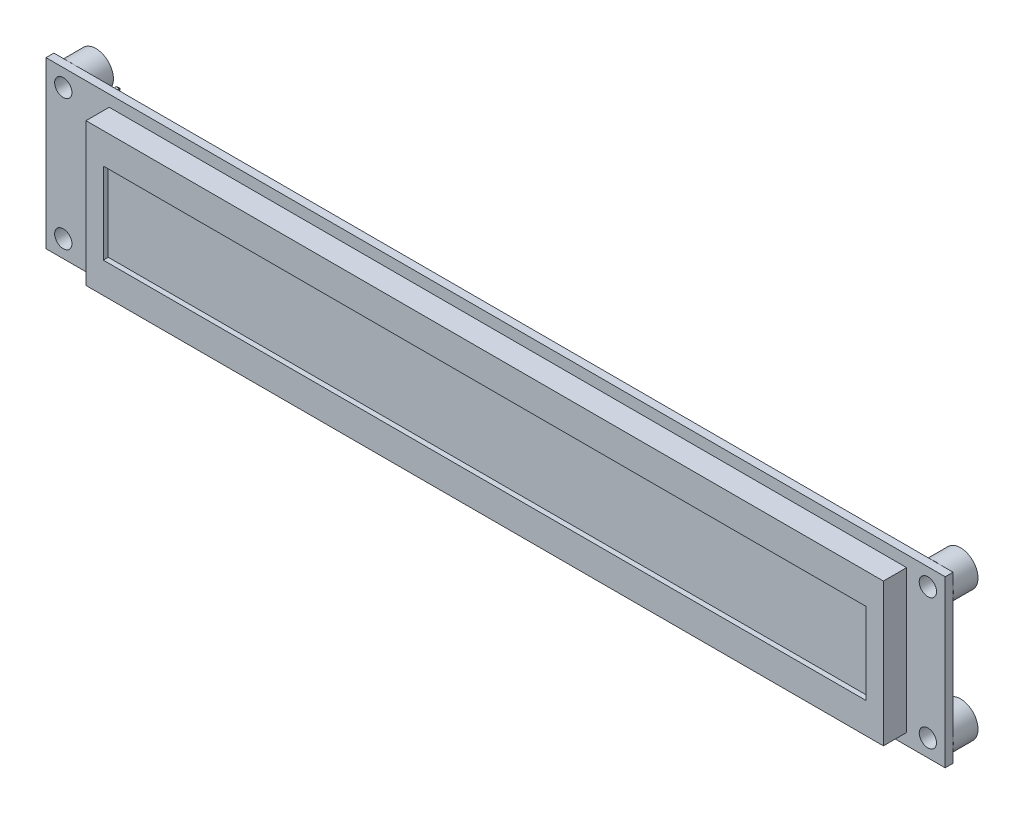
SolidWorks part; units mm, degrees
ref_plane "Спереди" through (0, 0, 0) normal (0, 0, 1) x (1, 0, 0)
ref_plane "Сверху" through (0, 0, 0) normal (0, 1, 0) x (1, 0, 0)
ref_plane "Справа" through (0, 0, 0) normal (1, 0, 0) x (0, 0, -1)
ref_plane "Плоскость4" through (0, 0, 5) normal (0, 0, 1) x (1, 0, 0)
sketch "Эскиз2" plane through (0, 0, 5) normal (0, 0, 1) x (1, 0, 0)
  line L1 (-91, -16.75) -> (91, -16.75)
  line L2 (-91, -16.75) -> (-91, 16.75)
  line L3 (-91, 16.75) -> (91, 16.75)
  line L4 (91, -16.75) -> (91, 16.75)
  line L5 (-91, -16.75) -> (91, 16.75) construction
  line L6 (-91, 16.75) -> (91, -16.75) construction
  point P0 (0, 0)
  dimension "D1" = 182
  dimension "D2" = 33.5
extrude "Бобышка-Вытянуть1" add sketch "Эскиз2" along normal blind 1.6
ref_plane "Плоскость5" through (0, 0, 0) normal (0, -1, 0) x (-1, 0, 0)
sketch "Эскиз3" plane through (0, 0, 6.6) normal (0, 0, 1) x (1, 0, 0)
  line L0 (-0.88, 0) -> (0.88, 0) construction
  line L1 (-78.2, 14.45) -> (83.2, 14.45)
  line L2 (-78.2, 14.45) -> (-78.2, -14.45)
  line L3 (-78.2, -14.45) -> (83.2, -14.45)
  line L4 (83.2, 14.45) -> (83.2, -14.45)
  line L5 (-78.2, 14.45) -> (83.2, -14.45) construction
  line L6 (-78.2, -14.45) -> (83.2, 14.45) construction
  line L7 (-91, 16.75) -> (-91, -16.75) construction
  point P0 (2.5, 0)
  dimension "D1" = 93.5
  dimension "D2" = 161.4
  dimension "D3" = 28.9
extrude "Бобышка-Вытянуть2" add sketch "Эскиз3" along normal blind 4.7
sketch "Эскиз4" plane through (0, 0, 11.3) normal (0, 0, 1) x (1, 0, 0)
  line L0 (-0.88, 0) -> (0.88, 0) construction
  line L1 (79.7, -8.25) -> (-74.7, -8.25)
  line L2 (79.7, -8.25) -> (79.7, 8.25)
  line L3 (79.7, 8.25) -> (-74.7, 8.25)
  line L4 (-74.7, -8.25) -> (-74.7, 8.25)
  line L5 (79.7, -8.25) -> (-74.7, 8.25) construction
  line L6 (79.7, 8.25) -> (-74.7, -8.25) construction
  line L7 (-91, 16.75) -> (-91, -16.75) construction
  point P0 (2.5, 0)
  dimension "D1" = 154.4
  dimension "D2" = 16.5
  dimension "D3" = 16.3
extrude "Вырез-Вытянуть1" cut sketch "Эскиз4" against normal blind 1
sketch "Эскиз5" plane through (0, 0, 6.6) normal (0, 0, 1) x (1, 0, 0)
  line L0 (-91, -16.75) -> (91, -16.75) construction
  line L1 (-91, 16.75) -> (-91, -16.75) construction
  circle A0 centre (-87.5, 13.25) radius 1.75
  circle A1 centre (-87.5, -13.25) radius 1.75
  circle A2 centre (87.5, -13.25) radius 1.75
  circle A3 centre (87.5, 13.25) radius 1.75
  dimension "D3" = 3.5
  dimension "D1" = 26.5
  dimension "D2" = 3.5
  dimension "D4" = 3.5
  dimension "D5" = 175
sketch "Эскиз6" plane through (0, 0, 5) normal (0, 0, -1) x (-1, 0, 0)
  circle A0 centre (-87.5, -13.25) radius 3.55
  circle A1 centre (-87.5, 13.25) radius 3.55
  circle A2 centre (87.5, 13.25) radius 3.55
  circle A3 centre (87.5, -13.25) radius 3.55
  dimension "D1" = 7.1
extrude "Бобышка-Вытянуть3" add sketch "Эскиз6" along normal blind 5
extrude "Вырез-Вытянуть2" cut sketch "Эскиз5" against normal through all
sketch "Эскиз7" plane through (0, 0, 0) normal (0, 0, 1) x (1, 0, 0)
  line L0 (-91, 12.6563) -> (-91, -12.6563) construction
  line L1 (-88.18, -8.51) -> (-88.82, -8.51)
  line L2 (-88.18, -8.51) -> (-88.18, -9.15)
  line L3 (-88.18, -9.15) -> (-88.82, -9.15)
  line L4 (-88.82, -8.51) -> (-88.82, -9.15)
  line L5 (-88.18, -8.51) -> (-88.82, -9.15) construction
  line L6 (-88.18, -9.15) -> (-88.82, -8.51) construction
  line L8 (-88.0937, 16.75) -> (-91, 16.75) construction
  point P0 (-88.5, -8.83)
  dimension "D1" = 0.64
  dimension "D2" = 0.64
  dimension "D3" = 2.5
  dimension "D4" = 25.58
extrude "Бобышка-Вытянуть4" add sketch "Эскиз7" against normal blind 3.2 separate body
chamfer "Фаска1" distance 0.2 angle 57 4 edges at (-88.18, -8.83, -3.2) (-88.5, -8.51, -3.2) (-88.82, -8.83, -3.2) (-88.5, -9.15, -3.2)
sketch "Эскиз9" plane through (0, 0, 0) normal (0, 0, 1) x (1, 0, 0)
  line L0 (-0.88, 0) -> (0.88, 0) construction
  line L1 (-89.73, 10.16) -> (-84.73, 10.16)
  line L2 (-89.73, 10.16) -> (-89.73, -10.16)
  line L3 (-89.73, -10.16) -> (-84.73, -10.16)
  line L4 (-84.73, 10.16) -> (-84.73, -10.16)
  line L5 (-89.73, 10.16) -> (-84.73, -10.16) construction
  line L6 (-89.73, -10.16) -> (-84.73, 10.16) construction
  point P0 (-87.23, 0)
  dimension "D1" = 5
  dimension "D2" = 20.32
  dimension "D3" = 1.27
extrude "Бобышка-Вытянуть5" add sketch "Эскиз9" along normal up to surface (5 mm away) up to face at (0, 0, 5)
pattern_linear "Линейный массив6" count 8 spacing 2.54 along (0, 1, 0) count 2 spacing 2.54 along (1, 0, 0) of "Бобышка-Вытянуть4", "Фаска1"
